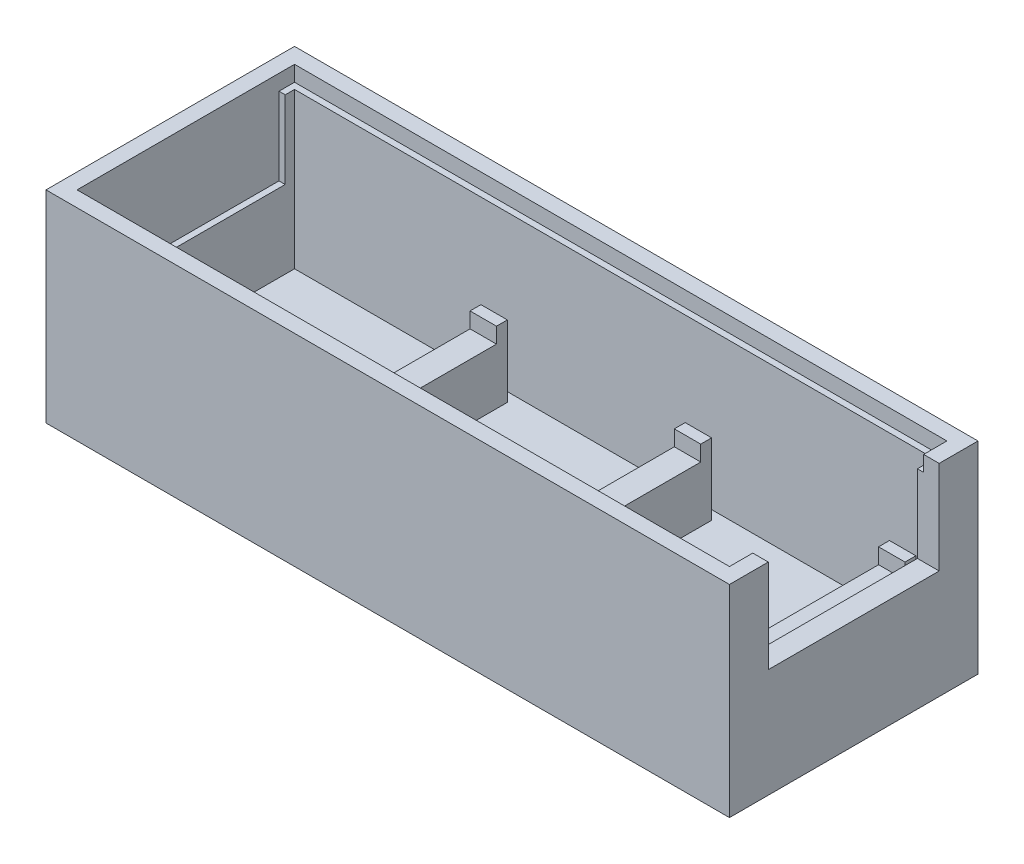
SolidWorks part; units mm, degrees
ref_plane "前视基准面" through (0, 0, 0) normal (0, 0, 1) x (1, 0, 0)
ref_plane "上视基准面" through (0, 0, 0) normal (0, 1, 0) x (1, 0, 0)
ref_plane "右视基准面" through (0, 0, 0) normal (1, 0, 0) x (0, 0, -1)
sketch "草图1" plane through (0, 0, 0) normal (0, 1, 0) x (1, 0, 0)
  line L1 (-22, 8) -> (22, 8)
  line L2 (-22, 8) -> (-22, -8)
  line L3 (-22, -8) -> (22, -8)
  line L4 (22, 8) -> (22, -8)
  line L5 (-22, 8) -> (22, -8) construction
  line L6 (-22, -8) -> (22, 8) construction
  point P0 (0, 0)
extrude "凸台-拉伸1" add sketch "草图1" against normal blind 2 contours L2 L1 L4 L3
sketch "草图2" plane through (0, -2, 0) normal (0, -1, 0) x (1, 0, 0)
  line L0 (-22, -8) -> (-22, 8) construction
  line L1 (-20, 6) -> (20, 6)
  line L2 (-20, 6) -> (-20, -6)
  line L3 (-20, -6) -> (20, -6)
  line L4 (20, 6) -> (20, -6)
  line L5 (-22, 8) -> (22, 8) construction
  line L6 (-22, -8) -> (22, -8) construction
  line L7 (22, -8) -> (22, 8) construction
  line L8 (-22, -8) -> (-22, 8)
  line L9 (-22, 8) -> (22, 8)
  line L10 (-22, -8) -> (22, -8)
  line L11 (22, -8) -> (22, 8)
  dimension "D1" = 12
  dimension "D2" = 40
  dimension "D3" = 2
  dimension "D4" = 2
extrude "凸台-拉伸2" add sketch "草图2" along normal blind 10
sketch "草图3" plane through (-22, 0, 0) normal (-1, 0, 0) x (0, 0, 1)
  line L0 (0, 0) -> (0, -12)
  line L1 (-5.5, -7) -> (5.5, -7)
  line L2 (-5.5, -7) -> (-5.5, -11)
  line L3 (-5.5, -11) -> (5.5, -11)
  line L4 (5.5, -7) -> (5.5, -11)
  line L5 (-5.5, -7) -> (5.5, -11) construction
  line L6 (-5.5, -11) -> (5.5, -7) construction
  line L7 (8, -12) -> (-8, -12) construction
  line L8 (-8, 0) -> (8, 0) construction
  point P0 (0, -9)
  dimension "D1" = 4
  dimension "D2" = 11
  dimension "D3" = 7
extrude "切除-拉伸1" cut sketch "草图3" against normal blind 2 contours L4 L1 L0 L3 | L2 L3 L0 L1
sketch "草图4" plane through (0, -2, 0) normal (0, -1, 0) x (1, 0, 0)
  line L0 (-20, -6) -> (20, -6) construction
  line L1 (-20, 6) -> (8, 6)
  line L2 (-20, 6) -> (-20, -6)
  line L3 (-20, -6) -> (8, -6)
  line L4 (8, 6) -> (8, -6)
  line L5 (20, -6) -> (20, 6) construction
  line L6 (-5.15, 6) -> (-6.85, 6)
  line L7 (-20, 6) -> (-18.3, 6)
  line L8 (-20, 6) -> (-20, -6)
  line L9 (-20, -6) -> (-18.3, -6)
  line L10 (-18.3, 6) -> (-18.3, -6)
  line L11 (8, 6) -> (6.3, 6)
  line L12 (8, 6) -> (8, -6)
  line L13 (8, -6) -> (6.3, -6)
  line L14 (6.3, 6) -> (6.3, -6)
  line L15 (-5.15, 6) -> (-5.15, -6)
  line L16 (-5.15, -6) -> (-6.85, -6)
  line L17 (-6.85, 6) -> (-6.85, -6)
  line M6 (-20, -6) -> (20, -6)
  line M8 (20, 6) -> (-20, 6)
  dimension "D1" = 12
  dimension "D2" = 1.7
  dimension "D3" = 1.7
  dimension "D4" = 0
  dimension "D5" = 24.6
  dimension "D6" = 11.45
  dimension "D7" = 11.45
extrude "凸台-拉伸4" add sketch "草图4" along normal blind 4.6 contours L14 L4 M8 M6 | L8 L7 L10 L9 | L6 L17 L16 L15
sketch "草图9" plane through (0, -12, 0) normal (0, -1, 0) x (1, 0, 0)
  line L0 (-22, 8) -> (-22, -8) construction
  line L1 (21, -7) -> (-21, -7)
  line L2 (21, -7) -> (21, 7)
  line L3 (21, 7) -> (-21, 7)
  line L4 (-21, -7) -> (-21, 7)
  line L5 (21, -7) -> (-21, 7) construction
  line L6 (21, 7) -> (-21, -7) construction
  line L7 (22, 8) -> (-22, 8) construction
  line L8 (22, -8) -> (22, 8) construction
  line L9 (-22, -8) -> (22, -8) construction
  line L10 (22, -8) -> (22, 8)
  line L11 (-22, -8) -> (22, -8)
  line L12 (-22, 8) -> (-22, -8)
  line L13 (22, 8) -> (-22, 8)
  point P0 (0, 0)
  dimension "D1" = 1
  dimension "D2" = 1
extrude "凸台-拉伸5" add sketch "草图9" along normal blind 1
sketch "草图11" plane through (0, -12, 0) normal (0, -1, 0) x (1, 0, 0)
  line L7 (-20, -6) -> (20, -6) construction
  line L8 (-20, -6) -> (21, -6)
  line L9 (21, -7) -> (21, 7) construction
sketch "草图12" plane through (0, -12, 0) normal (0, -1, 0) x (1, 0, 0)
  line L1 (20, 6) -> (21, 6)
  line L2 (20, 6) -> (20, -6)
  line L3 (20, -6) -> (21, -6)
  line L4 (21, 6) -> (21, -6)
extrude "切除-拉伸3" cut sketch "草图12" against normal blind 5
sketch "草图13" plane through (0, -13, 0) normal (0, -1, 0) x (1, 0, 0)
  line L1 (-20.6, -6.6) -> (20.6, -6.6)
  line L2 (-20.6, -6.6) -> (-20.6, 6.6)
  line L3 (-20.6, 6.6) -> (20.6, 6.6)
  line L4 (20.6, -6.6) -> (20.6, 6.6)
  line L5 (-20, -6) -> (20, -6)
  line L6 (-20, -6) -> (-20, 6)
  line L7 (-20, 6) -> (20, 6)
  line L8 (20, -6) -> (20, 6)
extrude "RevB_AssemblyClearance_41p2x13p2" cut sketch "草图13" against normal blind 11
sketch "草图14" plane through (-22, 0, 0) normal (-1, 0, 0) x (0, 0, 1)
  line L1 (-5.5, -14) -> (5.5, -14)
  line L2 (-5.5, -14) -> (-5.5, -7)
  line L3 (-5.5, -7) -> (5.5, -7)
  line L4 (5.5, -14) -> (5.5, -7)
extrude "RevB_USB_TopLoading_Uslot" cut sketch "草图14" against normal blind 2.1
sketch "草图17" plane through (8, 0, 0) normal (1, 0, 0) x (0, 0, -1)
  line L1 (-5.3, -6.61) -> (5.3, -6.61)
  line L2 (-5.3, -6.61) -> (-5.3, -5.6)
  line L3 (-5.3, -5.6) -> (5.3, -5.6)
  line L4 (5.3, -6.61) -> (5.3, -5.6)
extrude "RevB_UndersideSolderRelief_1mm" cut sketch "草图17" against normal blind 28
move or copy body "RevB_DefaultOrientation_OpeningPlusY" bodies to move or copy 112 copy no rotation origin (0, 0, 0) rotation axis (0, 0, 1) rotation angle 180
